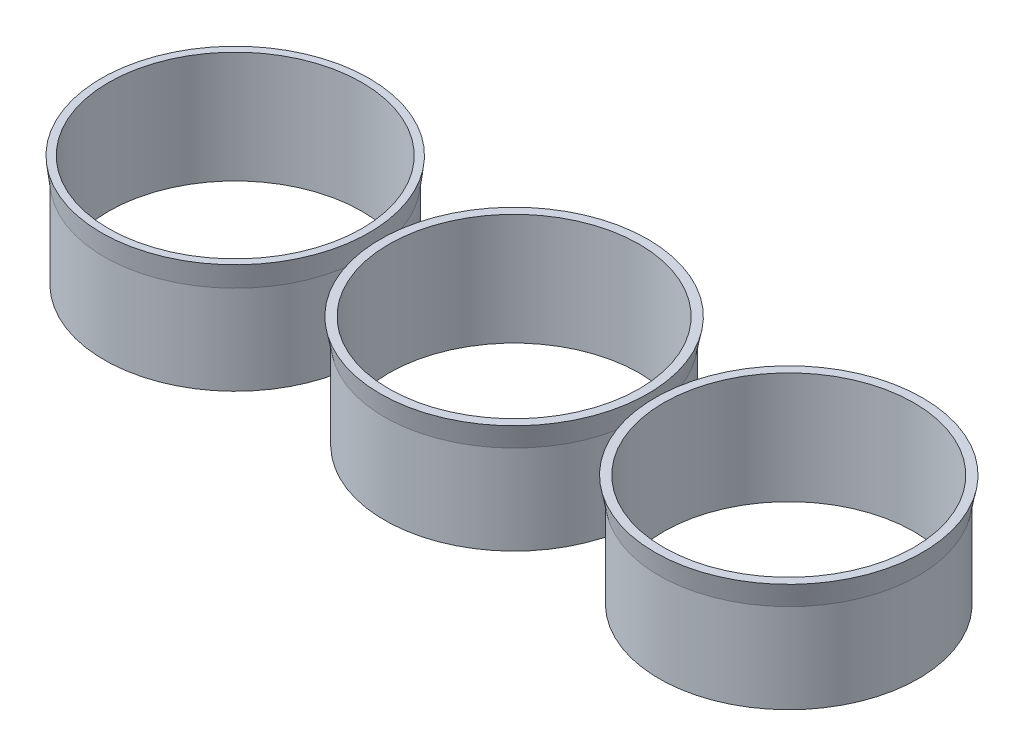
SolidWorks part; units mm, degrees
ref_plane "Front Plane" through (0, 0, 0) normal (0, 0, 1) x (1, 0, 0)
ref_plane "Top Plane" through (0, 0, 0) normal (0, 1, 0) x (1, 0, 0)
ref_plane "Right Plane" through (0, 0, 0) normal (1, 0, 0) x (0, 0, -1)
sketch "Sketch2" plane through (0, 0, 0) normal (0, 0, 1) x (1, 0, 0)
  line L0 (22.7, 0) -> (22.7, 20)
  line L1 (22.7, 20) -> (24, 20)
  line L2 (24, 20) -> (23.5, 16)
  line L3 (23.5, 16) -> (23.5, 0)
  line L4 (23.5, 0) -> (22.7, 0)
  line L5 (0, 0) -> (0, 20) construction
  line L6 (-23.5, 0) -> (-22.7, 0) construction
  line L7 (-23.5, 16) -> (-23.5, 0) construction
  line L8 (-24, 20) -> (-23.5, 16) construction
  line L9 (-22.7, 20) -> (-24, 20) construction
  line L10 (-22.7, 0) -> (-22.7, 20) construction
  point P8 (0, 0)
  point P14 (-23.5, 15.4115)
  point P15 (0, 0)
  dimension "D1" = 0.8
  dimension "D2" = 47
  dimension "D3" = 20
  dimension "D4" = 4
  dimension "D5" = 48
revolve "Revolve1" add sketch "Sketch2" angle 360 about L5
sketch "Sketch3" plane through (0, 0, 0) normal (0, 0, 1) x (1, 0, 0)
  line L0 (73.25, 0) -> (73.25, 16)
  line L1 (73.25, 16) -> (74, 20)
  line L2 (74, 20) -> (72.45, 20)
  line L3 (72.45, 20) -> (72.45, 0)
  line L4 (72.45, 0) -> (73.25, 0)
  line L5 (50, 0) -> (50, 20) construction
  line L6 (27.55, 0) -> (26.75, 0) construction
  line L7 (27.55, 20) -> (27.55, 0) construction
  line L8 (26, 20) -> (27.55, 20) construction
  line L9 (26.75, 16) -> (26, 20) construction
  line L10 (26.75, 0) -> (26.75, 16) construction
  point P13 (50, 20)
  point P14 (68.8359, 20)
  point P15 (0, 0)
  point P16 (0, 0)
  point P17 (50, 17.4374)
  point P18 (0, 0)
  dimension "D1" = 46.5
  dimension "D2" = 0.8
  dimension "D3" = 48
  dimension "D4" = 4
  dimension "D5" = 20
  dimension "D6" = 50
revolve "Revolve2" add sketch "Sketch3" angle 360 about L5
sketch "Sketch4" plane through (0, 0, 0) normal (0, 0, 1) x (1, 0, 0)
  line L0 (122.5, 0) -> (122.5, 16)
  line L1 (122.5, 16) -> (123.25, 20)
  line L2 (123.25, 20) -> (121.7, 20)
  line L3 (121.7, 20) -> (121.7, 0)
  line L4 (121.7, 0) -> (122.5, 0)
  line L5 (99.25, 0) -> (99.25, 20) construction
  line L6 (76.8, 0) -> (76, 0) construction
  line L7 (76.8, 20) -> (76.8, 0) construction
  line L8 (75.25, 20) -> (76.8, 20) construction
  line L9 (76, 16) -> (75.25, 20) construction
  line L10 (76, 0) -> (76, 16) construction
  point P7 (0, 0)
  point P8 (0, 0)
  point P10 (0, 0)
  point P16 (99.2226, 20.388)
  point P17 (78.1315, 20)
  dimension "D1" = 20
  dimension "D2" = 4
  dimension "D3" = 48
  dimension "D4" = 0.8
  dimension "D5" = 46.5
  dimension "D6" = 2
revolve "Revolve3" add sketch "Sketch4" angle 360 about L5
